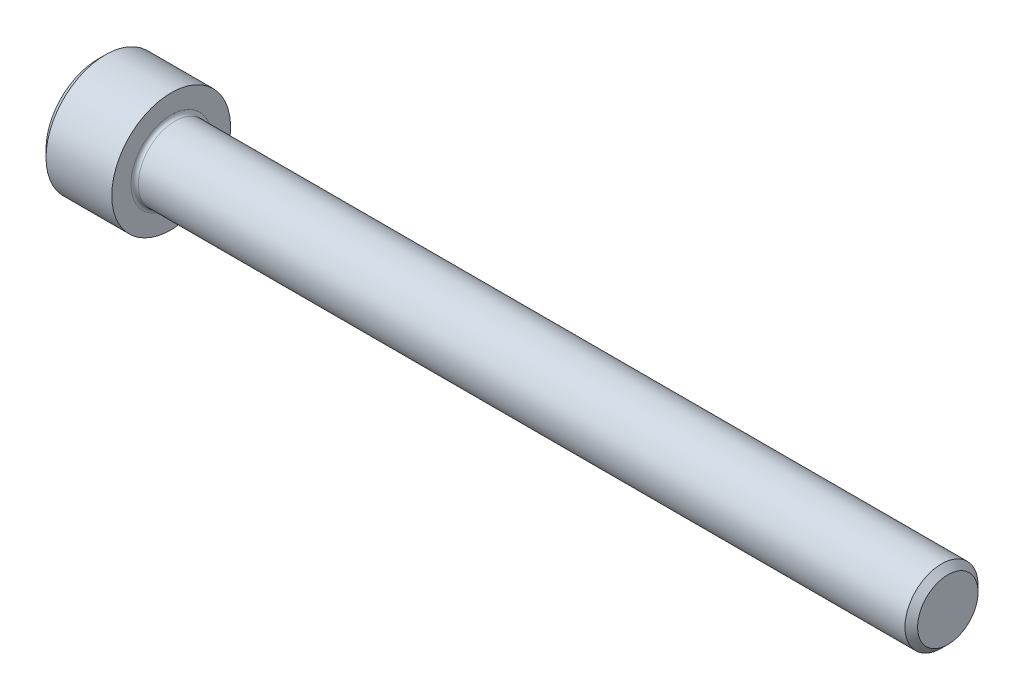
SolidWorks part; units mm, degrees
revolve "Base-Revolve" add sketch "BodySke"
sketch "BodySke" plane through (0, 0, 0) normal (0, 0, 1) x (1, 0, 0)
  line L0 (0, 0) -> (0, 5.7)
  line L1 (0.8, 6.5) -> (8, 6.5)
  line L2 (8, 6.5) -> (8, 4)
  line L3 (8, 4) -> (92.3095, 4)
  line L4 (93, 3.3095) -> (93, 0)
  line L5 (93, 0) -> (0, 0)
  line L6 (-31.75, 0) -> (127, 0) construction
  line L7 (0, 5.7) -> (0.8, 6.5)
  line L8 (93, 3.3095) -> (92.3095, 4)
  line L9 (0, -5.7) -> (0.8, -6.5) construction
  line L10 (93, -3.3095) -> (92.3095, -4) construction
  line L11 (9.25, 9.525) -> (9.25, 3.175) construction
  line L12 (73, 9.525) -> (73, 3.175) construction
  line L13 (43, 9.525) -> (43, 3.175) construction
  dimension "Diameter" = 8
  dimension "Head_ht" = 8
  dimension "Length" = 85
  dimension "Body_ch_ang" = 45
  dimension "Head_dia" = 13
  dimension "Head_ch_ang" = 45
  dimension "Minor_dia" = 6.619
  dimension "Advance" = 1.25
  dimension "Thread_nom" = 20
  dimension "Thread_length" = 50
  dimension "Head_ch_ht" = 0.8
cosmetic thread "ThreadCosmetic"
fillet "Fillet1" radius 0.4 1 edges at (8, 0, 4)
material "Plain Carbon Steel"
ref_plane "Plane1" through (0, 0, 0) normal (0, 0, 1) x (1, 0, 0)
ref_plane "Plane2" through (0, 0, 0) normal (0, 1, 0) x (1, 0, 0)
ref_plane "Plane3" through (0, 0, 0) normal (1, 0, 0) x (0, 0, -1)
sketch "Sketch2" plane through (0, 0, 0) normal (0, 0, 1) x (1, 0, 0)
  line L0 (0, 3.0475) -> (4, 3.0475)
  line L1 (4, 3.0475) -> (5.7595, 0)
  line L2 (-31.75, 0) -> (127, 0) construction
  line L3 (5.7595, 0) -> (0, 0)
  line L4 (0, 0) -> (0, 3.0475)
  line L5 (0, 5.7) -> (0, -5.7) construction
  line L6 (0, 0) -> (47.625, 0) construction
  line L7 (8, -6.5) -> (8, 6.5) construction
  dimension "D1" = 3.0475
  dimension "D2" = 60
revolve "Hex-PreBroach" cut sketch "Sketch2" angle 360 about L6
sketch "Sketch3" plane through (0, 0, 0) normal (-1, 0, 0) x (0, 0.5, 0.866)
  line L0 (1.7595, 3.0475) -> (-1.7595, 3.0475)
  line L1 (-1.7595, 3.0475) -> (-3.5189, 0)
  line L2 (1.7595, 3.0475) -> (3.5189, 0)
  line L3 (1.7595, -3.0475) -> (3.5189, 0)
  line L4 (1.7595, -3.0475) -> (-1.7595, -3.0475)
  line L5 (-1.7595, -3.0475) -> (-3.5189, 0)
  dimension "D1" = 3.0475
  dimension "D2" = 3.0475
  dimension "Hex_size" = 6.095
extrude "Hex" cut sketch "Sketch3" against normal blind 4
sketch "Sketch4" plane through (0, 0, 0) normal (-1, 0, 0) x (0, 0, 1)
  line L0 (0, 0) -> (3.7846, 0)
  line L1 (0, 0) -> (6.1484, 3.5498) construction
  line L2 (0, 0) -> (1.8923, 3.2776)
  line L3 (3.1235, 0.8061) -> (3.6229, 1.0945)
  line L4 (2.2599, 2.3019) -> (2.7593, 2.5903)
  arc A0 (3.1235, 0.8061) -> (2.2599, 2.3019) centre (0, 0) ccw
  arc A1 (3.7846, 0) -> (3.6229, 1.0945) centre (0, 0) ccw
  arc A2 (1.8923, 3.2776) -> (2.7593, 2.5903) centre (0, 0) cw
  dimension "D1" = 30
  dimension "D2" = 60
  dimension "Spline_p_dim" = 1.7272
  dimension "D3" = 0.8636
extrude "Spline" [suppressed] cut sketch "Sketch4" against normal blind 4
pattern_circular "CirPattern1" [suppressed] count 6 every 60
sketch "Sketch5" plane through (0, 0, 0) normal (0, 0, 1) x (1, 0, 0)
  line L0 (-31.75, 0) -> (127, 0) construction
  line L2 (0, 5.7) -> (0, -5.7) construction
  circle A0 centre (2.7, 0) radius 0.675
  dimension "Drilled_hole_dia" = 1.35
  dimension "Drilled_hole_loc" = 2.7
extrude "Hole" [suppressed] cut sketch "Sketch5" against normal through all and the other way through all
pattern_circular "Drilled-4" [suppressed] count 2 every 60
pattern_circular "Drilled-6" [suppressed] count 3 every 60
sketch "ThdSchSke" plane through (0, 0, 0) normal (0, 0, 1) x (1, 0, 0)
  line L0 (73, -3.3095) -> (72.5165, -4)
  line L1 (73, -3.3095) -> (73.4835, -4)
  line L2 (73.4835, -4) -> (73.4835, -5)
  line L3 (-3.175, 0) -> (5.1513, 0) construction
  line L5 (73.4835, -5) -> (72.5165, -5)
  line L6 (72.5165, -5) -> (72.5165, -4)
  line L7 (0, 5.7) -> (0, -5.7) construction
  dimension "Thread_minor" = 6.619
  dimension "Diameter" = 8
  dimension "Start" = 73
revolve "ThreadSchematic" [suppressed] cut sketch "ThdSchSke" angle 360 about L3
pattern_linear "ThdSchPat" [suppressed]
equation "\"D2@Sketch3\" = \"Hex_size@Sketch3\" / 2"
equation "\"D1@Sketch3\" = \"Hex_size@Sketch3\" / 2"
equation "\"D1@Sketch2\" = \"Hex_size@Sketch3\" / 2"
equation "\"D3@Sketch4\" = \"Spline_p_dim@Sketch4\" / 2"
equation "\"Thread_minor@ThreadCosmetic\"  =  \"Minor_dia@BodySke\""
equation "\"D2@CirPattern1\" = 360 / \"Num_teeth@CirPattern1\""
equation "\"Wall_thickness@Sketch2\" = \"Head_ht@BodySke\" - \"Key_eng@Hex\""
equation "\"Thread_length@ThreadCosmetic\" = ((sgn( (\"Length@BodySke\" - \"Advance@BodySke\" ) - \"Thread_nom@BodySke\" )-1)*( (\"Length@BodySke\" - \"Advance@BodySke\" ) - \"Thread_nom@BodySke\" ))/-2+ \"Thread_nom@BodySke\""
equation "\"Thread_minor@ThdSchSke\" = \"Minor_dia@BodySke\""
equation "\"Diameter@ThdSchSke\" = \"Diameter@BodySke\""
equation "\"Overcut@ThdSchSke\" = \"Diameter@BodySke\" * 1.25"
equation "\"Start@ThdSchSke\" = \"Head_ht@BodySke\" + \"Length@BodySke\" - \"Thread_length@ThreadCosmetic\"  '---Non-countersunk---"
equation "\"Num_threads@ThdSchPat\" = int( \"Thread_length@ThreadCosmetic\" / \"Advance@BodySke\" + 0.999 )  + 1"
equation "\"Advance@ThdSchPat\" = \"Thread_length@ThreadCosmetic\" /  (\"Num_threads@ThdSchPat\" - 1) 'relax it"
equation "\"Num_threads@ThdSchPat\" = \"Num_threads@ThdSchPat\" - sgn( \"Num_threads@ThdSchPat\" - 1) '---chamfered tips only---"
